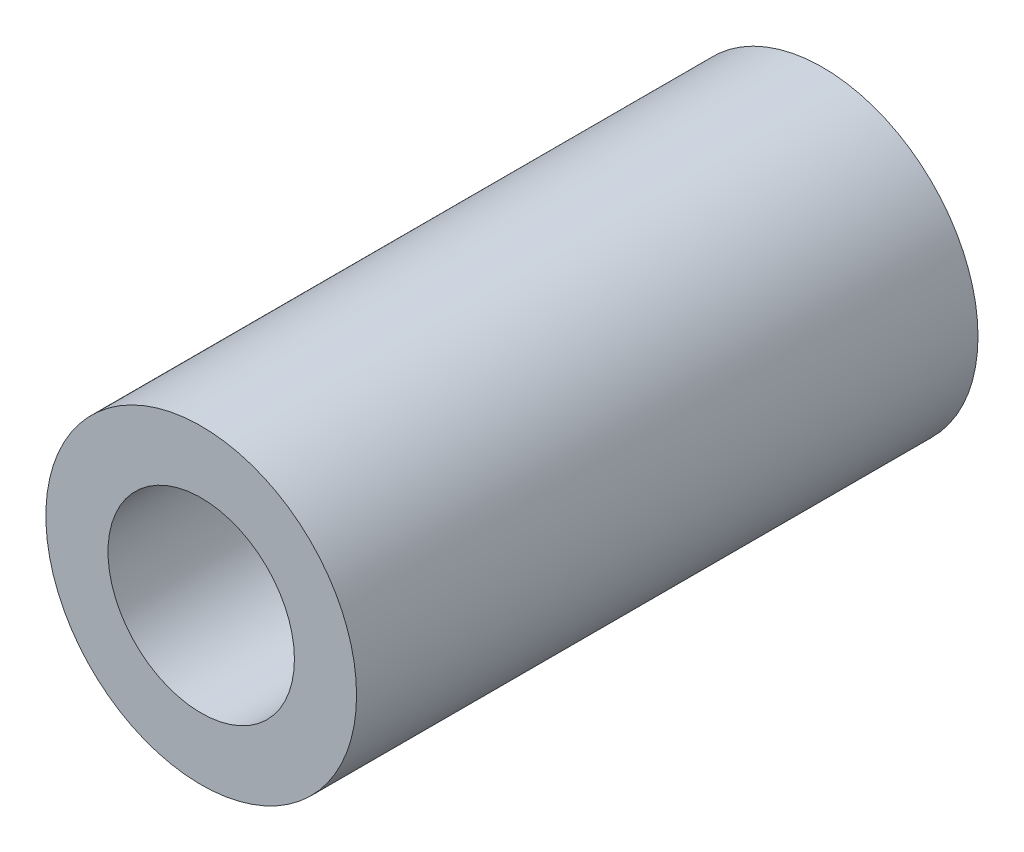
SolidWorks part; units mm, degrees
ref_plane "Front Plane" through (0, 0, 0) normal (0, 0, 1) x (1, 0, 0)
ref_plane "Top Plane" through (0, 0, 0) normal (0, 1, 0) x (1, 0, 0)
ref_plane "Right Plane" through (0, 0, 0) normal (1, 0, 0) x (0, 0, -1)
sketch "Sketch5" plane through (0, 0, 0) normal (0, 0, 1) x (1, 0, 0)
  circle A0 centre (0, 0) radius 2.5
  dimension "D1" = 5
extrude "Boss-Extrude2" add sketch "Sketch5" along normal blind 10
sketch "Sketch6" plane through (0, 0, 10) normal (0, 0, 1) x (1, 0, 0)
  circle A0 centre (0, 0) radius 1.5
  dimension "D1" = 3
extrude "Cut-Extrude1" cut sketch "Sketch6" against normal blind 10
